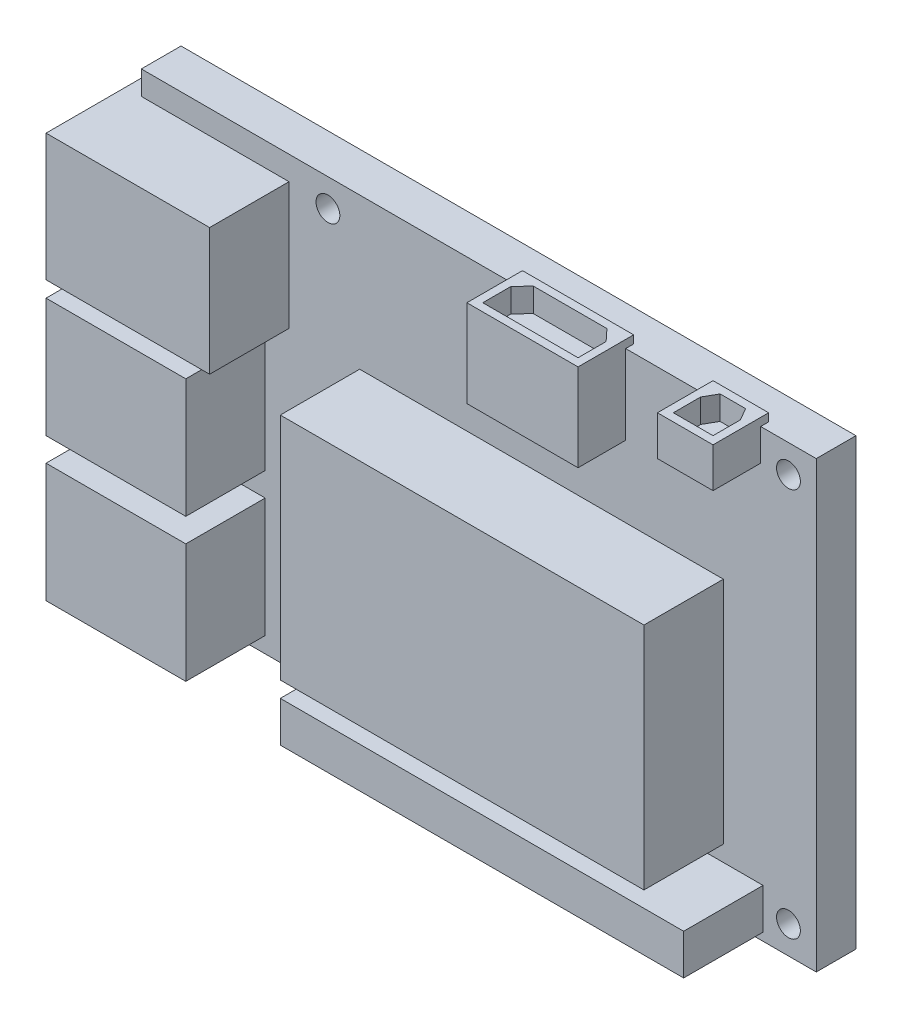
SolidWorks part; units mm, degrees
ref_plane "Alzado" through (0, 0, 0) normal (0, 0, 1) x (1, 0, 0)
ref_plane "Planta" through (0, 0, 0) normal (0, 1, 0) x (1, 0, 0)
ref_plane "Vista lateral" through (0, 0, 0) normal (1, 0, 0) x (0, 0, -1)
sketch "Croquis1" plane through (0, 0, 0) normal (0, 0, 1) x (1, 0, 0)
  line L1 (0, 56) -> (85, 56)
  line L2 (0, 56) -> (0, 0)
  line L3 (0, 0) -> (85, 0)
  line L4 (85, 56) -> (85, 0)
  circle A0 centre (23.5, 52.5) radius 1.5
  circle A1 centre (23.5, 3.5) radius 1.5
  circle A2 centre (81.5, 52.5) radius 1.5
  circle A3 centre (81.5, 3.5) radius 1.5
  dimension "D6" = 3
  dimension "D1" = 56
  dimension "D2" = 85
  dimension "D3" = 58
  dimension "D4" = 23.5
  dimension "D5" = 49
  dimension "D13" = 3.5
extrude "Saliente-Extruir3" add sketch "Croquis1" along normal blind 5
sketch "Croquis2" plane through (0, 0, 5) normal (0, 0, 1) x (1, 0, 0)
  line L0 (0, 56) -> (0, 0) construction
  line L1 (-2, 53) -> (18.6, 53)
  line L2 (-2, 53) -> (-2, 37)
  line L3 (-2, 37) -> (18.6, 37)
  line L4 (18.6, 53) -> (18.6, 37)
  line L5 (85, 56) -> (0, 56) construction
  dimension "D1" = 20.6
  dimension "D2" = 16
  dimension "D3" = 2
  dimension "D4" = 3
extrude "Saliente-Extruir4" add sketch "Croquis2" along normal blind 10 and the other way blind 3
sketch "Croquis3" plane through (0, 0, 5) normal (0, 0, 1) x (1, 0, 0)
  line L1 (27.5, 6.1) -> (78.3, 6.1)
  line L2 (27.5, 6.1) -> (27.5, 1)
  line L3 (27.5, 1) -> (78.3, 1)
  line L4 (78.3, 6.1) -> (78.3, 1)
  line L5 (85, 0) -> (85, 56) construction
  line L6 (0, 0) -> (85, 0) construction
  dimension "D1" = 50.8
  dimension "D2" = 5.1
  dimension "D3" = 6.7
  dimension "D4" = 1
extrude "Saliente-Extruir5" add sketch "Croquis3" along normal blind 10
sketch "Croquis4" plane through (-2, 0, 0) normal (-1, 0, 0) x (0, 0, 1)
  line L0 (15, 53) -> (15, 37) construction
  line L1 (3, 52) -> (14, 52)
  line L2 (3, 52) -> (3, 38)
  line L3 (3, 38) -> (14, 38)
  line L4 (14, 52) -> (14, 38)
  line L5 (2, 53) -> (2, 37) construction
  line L6 (2, 53) -> (15, 53) construction
  line L7 (2, 37) -> (15, 37) construction
  dimension "D1" = 1
  dimension "D2" = 1
  dimension "D3" = 1
  dimension "D4" = 1
extrude "Cortar-Extruir2" cut sketch "Croquis4" against normal blind 15
sketch "Croquis5" plane through (0, 0, 5) normal (0, 0, 1) x (1, 0, 0)
  line L1 (27.5, 37) -> (73.3, 37)
  line L2 (27.5, 37) -> (27.5, 8.1)
  line L3 (27.5, 8.1) -> (73.3, 8.1)
  line L4 (73.3, 37) -> (73.3, 8.1)
  line L6 (27.5, 6.1) -> (27.5, 1) construction
  line L7 (78.3, 1) -> (78.3, 6.1) construction
  line L8 (78.3, 6.1) -> (27.5, 6.1) construction
  line L9 (0, 37) -> (18.6, 37) construction
  dimension "D1" = 5
  dimension "D2" = 2
extrude "Saliente-Extruir6" add sketch "Croquis5" along normal blind 10
sketch "Croquis6" plane through (0, 0, 5) normal (0, 0, 1) x (1, 0, 0)
  line L0 (-2, 53) -> (-2, 37) construction
  line L1 (-2, 35) -> (15.6, 35)
  line L2 (-2, 35) -> (-2, 20)
  line L3 (-2, 20) -> (15.6, 20)
  line L4 (15.6, 35) -> (15.6, 20)
  line L5 (18.6, 37) -> (18.6, 53) construction
  line L6 (0, 37) -> (18.6, 37) construction
  line L8 (-2, 17) -> (15.6, 17)
  line L9 (-2, 17) -> (-2, 2)
  line L10 (-2, 2) -> (15.6, 2)
  line L11 (15.6, 17) -> (15.6, 2)
  dimension "D1" = 3
  dimension "D2" = 2
  dimension "D3" = 15
  dimension "D4" = 15
  dimension "D5" = 3
extrude "Saliente-Extruir8" add sketch "Croquis6" along normal blind 10 and the other way blind 3
sketch "Croquis7" plane through (-2, 0, 0) normal (-1, 0, 0) x (0, 0, 1)
  line L1 (3, 34) -> (8, 34)
  line L2 (3, 34) -> (3, 21)
  line L3 (3, 21) -> (8, 21)
  line L4 (8, 34) -> (8, 21)
  line L6 (2, 35) -> (15, 35) construction
  line L7 (2, 20) -> (15, 20) construction
  line L8 (2, 35) -> (2, 20) construction
  line L9 (15, 35) -> (15, 20) construction
  line L10 (9, 34) -> (14, 34)
  line L11 (9, 34) -> (9, 21)
  line L12 (9, 21) -> (14, 21)
  line L13 (14, 34) -> (14, 21)
  line L14 (2, 17) -> (15, 17) construction
  line L15 (14, 16) -> (9, 16)
  line L16 (14, 16) -> (14, 3)
  line L17 (14, 3) -> (9, 3)
  line L18 (9, 16) -> (9, 3)
  line L19 (2, 2) -> (15, 2) construction
  line L21 (8, 16) -> (3, 16)
  line L22 (8, 16) -> (8, 3)
  line L23 (8, 3) -> (3, 3)
  line L24 (3, 16) -> (3, 3)
  dimension "D1" = 5
  dimension "D2" = 1
  dimension "D3" = 1
  dimension "D4" = 1
  dimension "D5" = 1
  dimension "D6" = 5
  dimension "D7" = 1
  dimension "D8" = 1
extrude "Cortar-Extruir3" cut sketch "Croquis7" against normal blind 15
sketch "Croquis8" plane through (0, 0, 5) normal (0, 0, 1) x (1, 0, 0)
  line L0 (85, 0) -> (85, 56) construction
  line L1 (71, 57) -> (78, 57)
  line L2 (71, 57) -> (71, 52)
  line L3 (71, 52) -> (78, 52)
  line L4 (78, 57) -> (78, 52)
  line L5 (85, 56) -> (0, 56) construction
  line L7 (47, 57) -> (61, 57)
  line L8 (47, 57) -> (47, 46)
  line L9 (47, 46) -> (61, 46)
  line L10 (61, 57) -> (61, 46)
  dimension "D1" = 7
  dimension "D2" = 7
  dimension "D3" = 5
  dimension "D4" = 1
  dimension "D5" = 24
  dimension "D6" = 14
  dimension "D7" = 11
  dimension "D8" = 1
extrude "Saliente-Extruir9" add sketch "Croquis8" along normal blind 6 and the other way blind 1
sketch "Croquis9" plane through (0, 57, 0) normal (0, 1, 0) x (1, 0, 0)
  line L0 (48, -10) -> (60, -10)
  line L1 (60, -10) -> (60, -6.4621)
  line L2 (60, -6.4621) -> (58.6354, -5)
  line L3 (58.6354, -5) -> (49.3646, -5)
  line L4 (49.3646, -5) -> (48, -6.4621)
  line L5 (48, -6.4621) -> (48, -10)
  line L6 (61, -11) -> (47, -11) construction
  line L7 (61, -4) -> (47, -4) construction
  line L8 (47, -4) -> (47, -11) construction
  line L9 (61, -4) -> (61, -11) construction
  line L10 (72, -10) -> (77, -10)
  line L11 (77, -10) -> (77, -6.5618)
  line L12 (77, -6.5618) -> (76.1052, -5)
  line L13 (76.1052, -5) -> (72.8948, -5)
  line L14 (72.8948, -5) -> (72, -6.5618)
  line L15 (72, -6.5618) -> (72, -10)
  line L16 (78, -4) -> (71, -4) construction
  line L17 (71, -4) -> (71, -11) construction
  line L18 (78, -4) -> (78, -11) construction
  point P2 (54, -11)
  dimension "D1" = 2
  dimension "D2" = 2
  dimension "D3" = 1
  dimension "D4" = 1
  dimension "D5" = 3.5379
  dimension "D6" = 1
  dimension "D7" = 1
  dimension "D8" = 1.8
  dimension "D9" = 1.8
  dimension "D10" = 1
  dimension "D11" = 1
  dimension "D12" = 1
  dimension "D13" = 3.2103
extrude "Cortar-Extruir4" cut sketch "Croquis9" against normal blind 3
